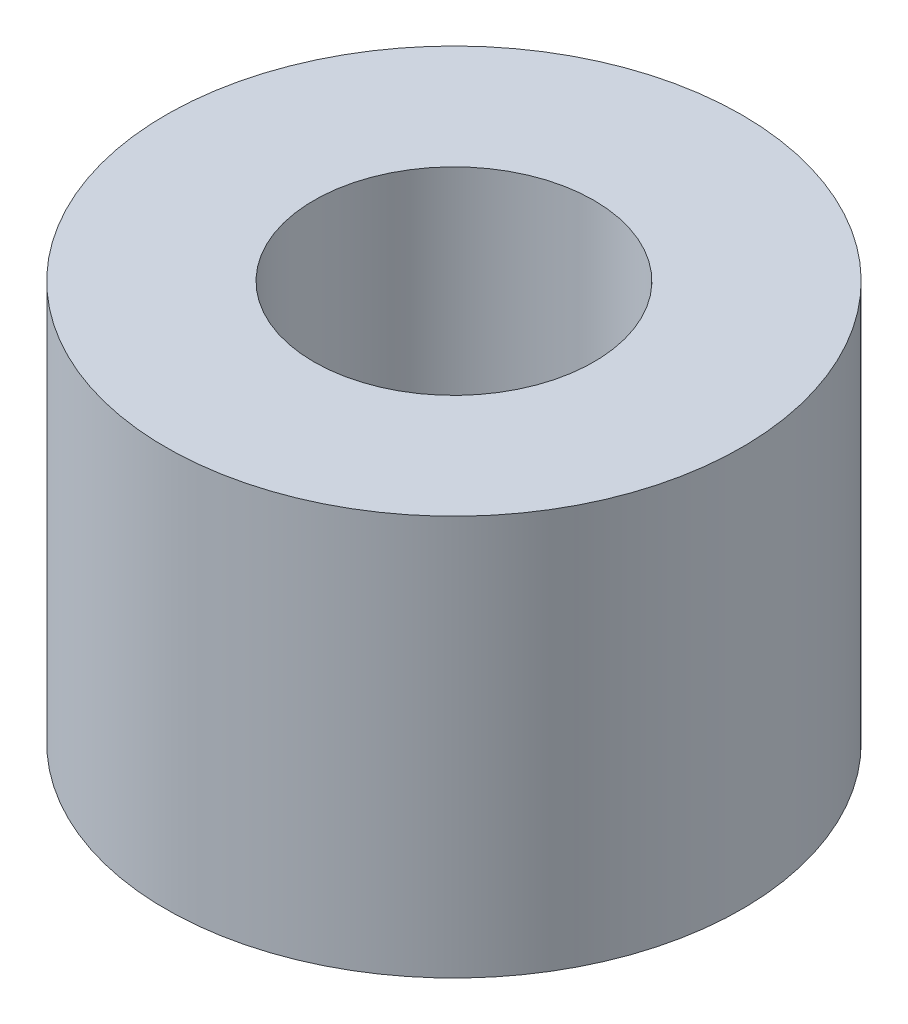
SolidWorks part; units mm, degrees
ref_plane "Front Plane" through (0, 0, 0) normal (0, 0, 1) x (1, 0, 0)
ref_plane "Top Plane" through (0, 0, 0) normal (0, 1, 0) x (1, 0, 0)
ref_plane "Right Plane" through (0, 0, 0) normal (1, 0, 0) x (0, 0, -1)
ref_plane "Plane1"
sketch "Sketch1" plane through (0, 0, 0) normal (0, 1, 0) x (-1, 0, 0)
  circle A0 centre (0, 0) radius 4.572
  circle A1 centre (0, 0) radius 2.2225
  dimension "D1" = 4.445
  dimension "D2" = 9.144
extrude "Extrusion1" add sketch "Sketch1" along normal blind 6.35 contours A0 A1
